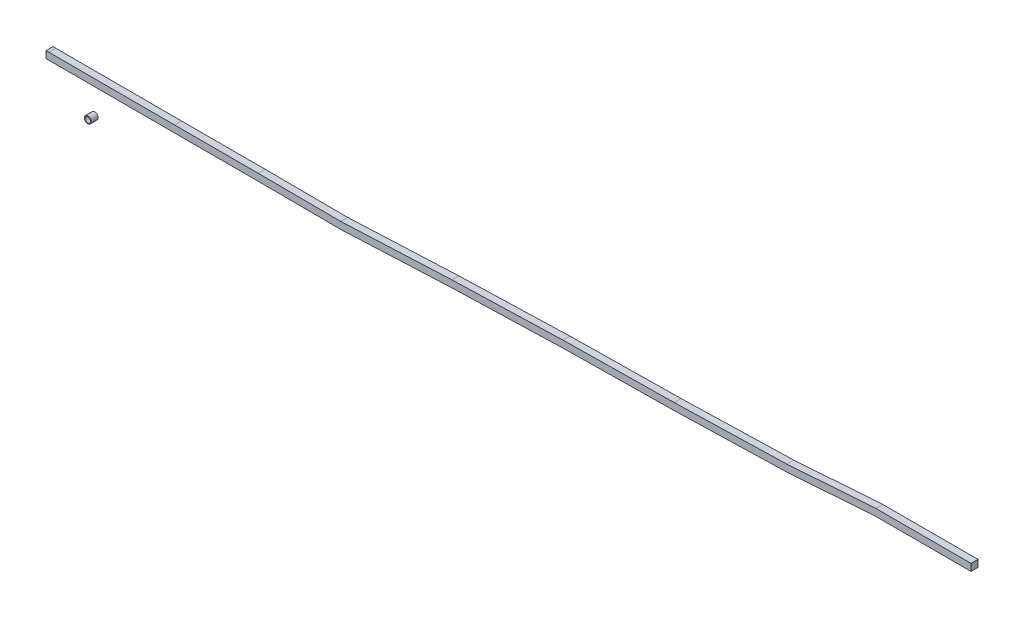
SolidWorks part; units mm, degrees
ref_plane "前视基准面" through (0, 0, 0) normal (0, 0, 1) x (1, 0, 0)
ref_plane "上视基准面" through (0, 0, 0) normal (0, 1, 0) x (1, 0, 0)
ref_plane "右视基准面" through (0, 0, 0) normal (1, 0, 0) x (0, 0, -1)
sketch "Model" plane through (0, 0, 0) normal (0, 0, 1) x (1, 0, 0)
  line L0 (639.3851, -46.8138) -> (703.5284, -42.4208)
  line L1 (703.5284, -42.4208) -> (771.9717, -42.4208)
  line L2 (558.3447, -48.9897) -> (639.3851, -46.8138)
  line L3 (478.3851, -50.081) -> (558.3447, -48.9897)
  line L4 (398.3501, -52.5032) -> (478.3851, -50.081)
  line L5 (318.3791, -56.0946) -> (398.3501, -52.5032)
  line L6 (108.3224, -55.6665) -> (198.7723, -55.7619)
  line L7 (198.7723, -55.7619) -> (259.1297, -55.7619)
  line L8 (259.1297, -55.7619) -> (318.3791, -56.0946)
  line L9 (108.3224, -55.6665) -> (106.3224, -55.6665)
  line L10 (639.3851, -41.8138) -> (703.5284, -37.4208)
  line L11 (703.5284, -37.4208) -> (771.9717, -37.4208)
  line L12 (558.3447, -43.9897) -> (639.3851, -41.8138)
  line L13 (478.3851, -45.081) -> (558.3447, -43.9897)
  line L14 (398.3501, -47.5032) -> (478.3851, -45.081)
  line L15 (318.3791, -51.0946) -> (398.3501, -47.5032)
  line L16 (108.3224, -50.6665) -> (198.7723, -50.7619)
  line L17 (198.7723, -50.7619) -> (259.1297, -50.7619)
  line L18 (259.1297, -50.7619) -> (318.3791, -51.0946)
  line L19 (108.3224, -50.6665) -> (106.3224, -50.6665)
  line L20 (106.3224, -50.6665) -> (106.3224, -55.6665)
  line L21 (771.9717, -37.4208) -> (771.9717, -42.4208)
  circle A0 centre (136.3527, -78.7729) radius 2
  circle A1 centre (136.3527, -78.7729) radius 2.5
extrude "凸台-拉伸1" add sketch "Model" along normal blind 5
